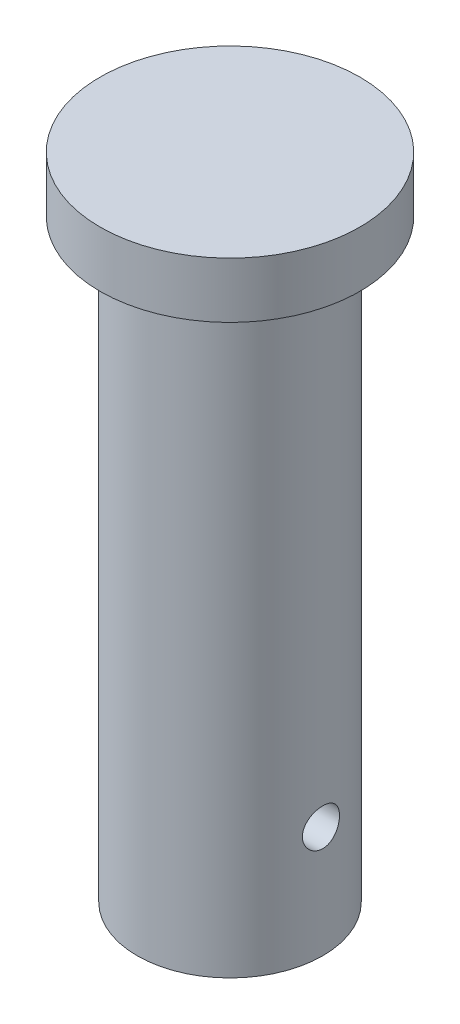
SolidWorks part; units mm, degrees
ref_plane "Front Plane" through (0, 0, 0) normal (0, 0, 1) x (1, 0, 0)
ref_plane "Top Plane" through (0, 0, 0) normal (0, 1, 0) x (1, 0, 0)
ref_plane "Right Plane" through (0, 0, 0) normal (1, 0, 0) x (0, 0, -1)
sketch "Sketch1" plane through (0, 0, 0) normal (0, 0, 1) x (1, 0, 0)
  line L0 (0, 0) -> (0, 175)
  line L1 (0, 175) -> (35, 175)
  line L2 (35, 175) -> (35, 160)
  line L3 (35, 160) -> (25, 160)
  line L4 (25, 160) -> (25, 0)
  line L5 (25, 0) -> (0, 0)
  dimension "D1" = 15
  dimension "D2" = 35
  dimension "D3" = 25
  dimension "D4" = 160
revolve "Revolve1" add sketch "Sketch1" angle 360 about L0
ref_plane "Plane1" through (25, 0, 0) normal (1, 0, 0) x (0, 0, -1)
sketch "Sketch2" plane through (25, 0, 0) normal (1, 0, 0) x (0, 0, -1)
  circle A0 centre (0, 30) radius 5
  dimension "D2" = 10
  dimension "D1" = 30
extrude "Cut-Extrude1" cut sketch "Sketch2" against normal through all
